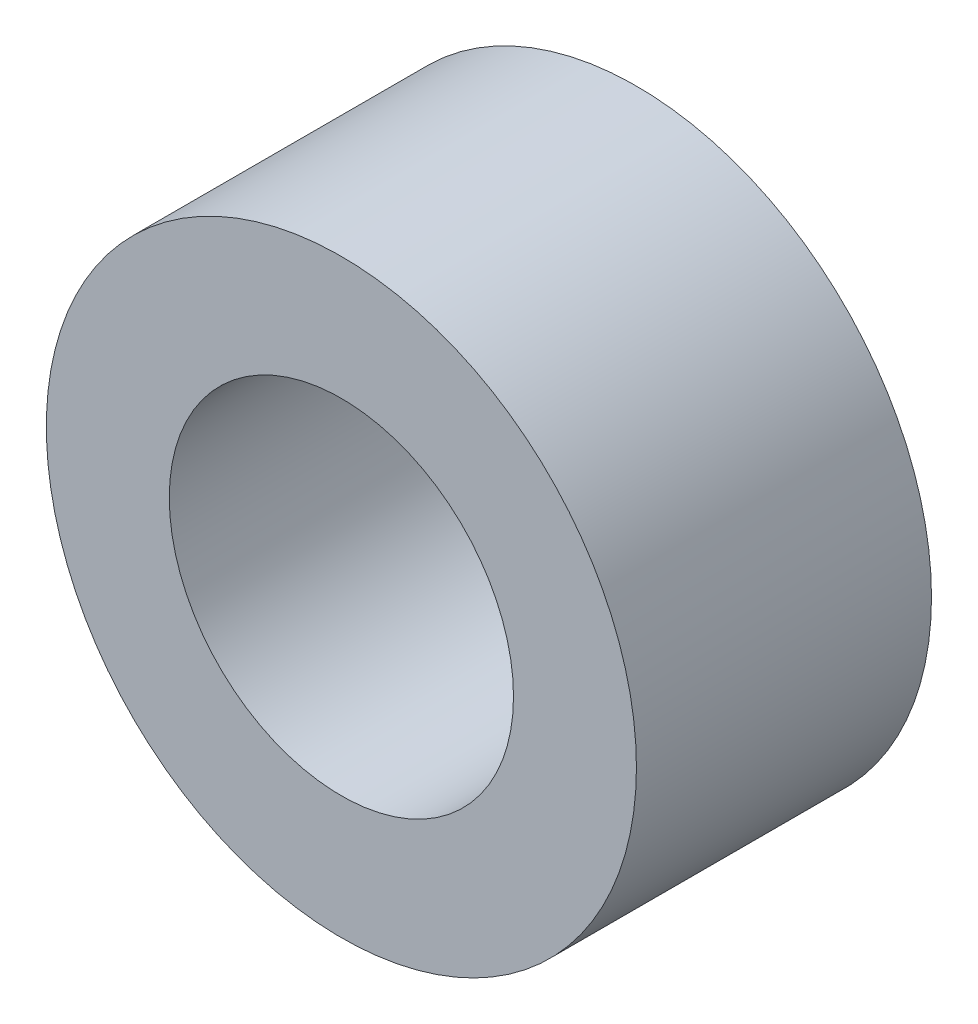
SolidWorks part; units mm, degrees
ref_plane "Front Plane" through (0, 0, 0) normal (0, 0, 1) x (1, 0, 0)
ref_plane "Top Plane" through (0, 0, 0) normal (0, 1, 0) x (1, 0, 0)
ref_plane "Right Plane" through (0, 0, 0) normal (1, 0, 0) x (0, 0, -1)
sketch "Sketch1" plane through (0, 0, 0) normal (0, 0, 1) x (1, 0, 0)
  circle A0 centre (0, 0) radius 1.75
  circle A1 centre (0, 0) radius 3
  dimension "D1" = 3.5
  dimension "D2" = 6
extrude "Boss-Extrude1" add sketch "Sketch1" along normal blind 3
